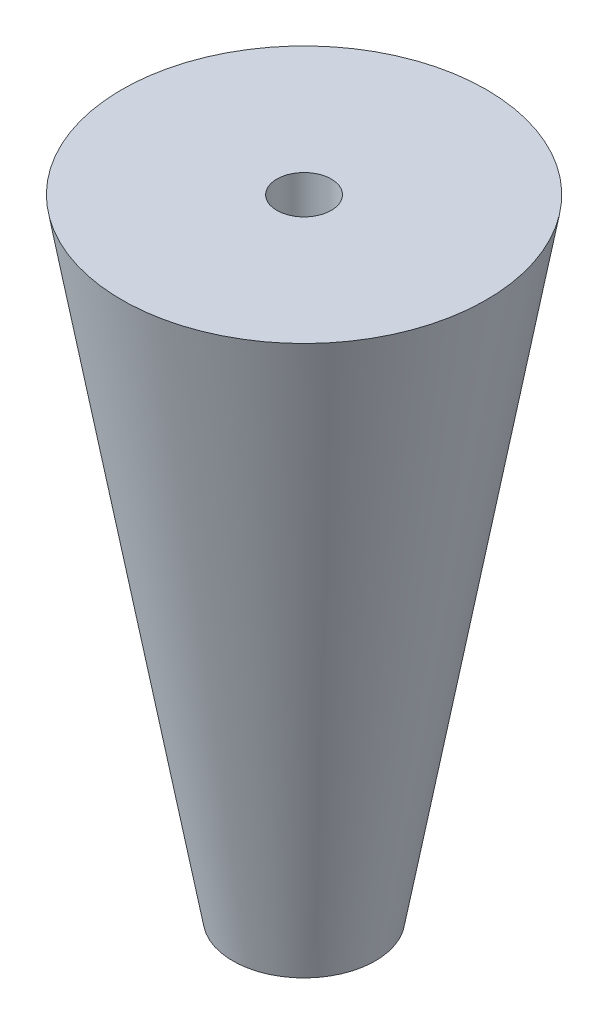
SolidWorks part; units mm, degrees
ref_plane "Front Plane" through (0, 0, 0) normal (0, 0, 1) x (1, 0, 0)
ref_plane "Top Plane" through (0, 0, 0) normal (0, 1, 0) x (1, 0, 0)
ref_plane "Right Plane" through (0, 0, 0) normal (1, 0, 0) x (0, 0, -1)
sketch "Sketch1" plane through (0, 0, 0) normal (0, 0, 1) x (1, 0, 0)
  line L0 (116.443, 23.733) -> (116.443, 133.6585)
  line L1 (116.443, 133.6585) -> (84.5403, 133.6585)
  line L2 (84.5403, 133.6585) -> (103.9593, 23.733)
  line L3 (103.9593, 23.733) -> (116.443, 23.733)
revolve "Revolve1" add sketch "Sketch1" angle 360 about L0
sketch "Sketch2" plane through (0, 23.733, 0) normal (0, -1, 0) x (1, 0, 0)
  circle A0 centre (116.443, 0) radius 4.7625
  dimension "D1" = 9.525
extrude "Cut-Extrude1" cut sketch "Sketch2" against normal through all
